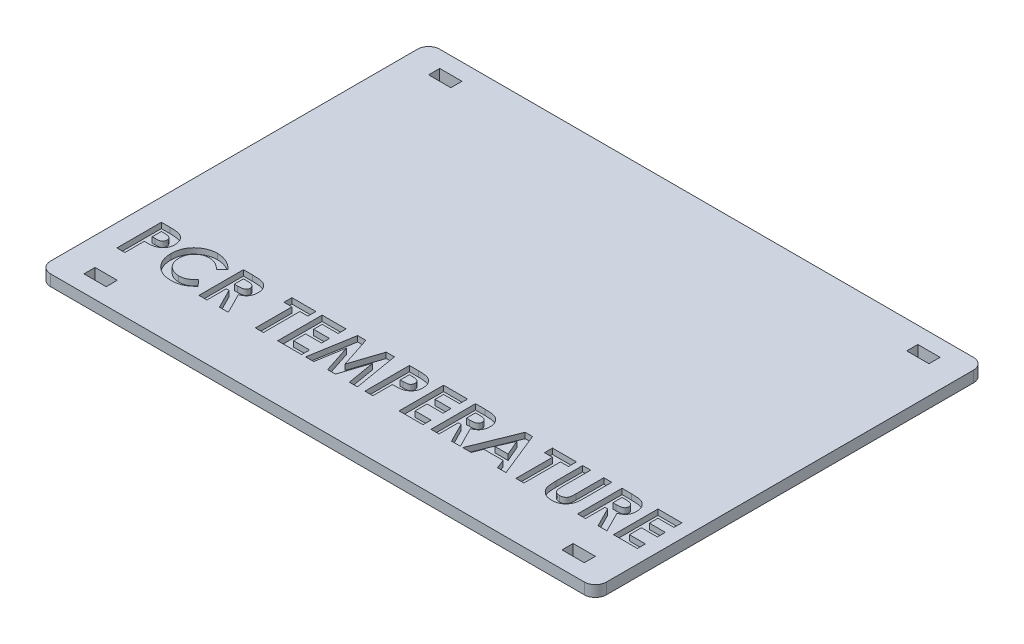
SolidWorks part; units mm, degrees
ref_plane "Front Plane" through (0, 0, 0) normal (0, 0, 1) x (1, 0, 0)
ref_plane "Top Plane" through (0, 0, 0) normal (0, 1, 0) x (1, 0, 0)
ref_plane "Right Plane" through (0, 0, 0) normal (1, 0, 0) x (0, 0, -1)
sketch "Sketch1" plane through (0, 0, 0) normal (0, 1, 0) x (1, 0, 0)
  line L1 (-48, 35) -> (48, 35)
  line L2 (-50, 33) -> (-50, -33)
  line L3 (-48, -35) -> (48, -35)
  line L4 (50, 33) -> (50, -33)
  line L5 (-50, 35) -> (50, -35) construction
  line L6 (-50, -35) -> (50, 35) construction
  arc A0 (-50, -33) -> (-48, -35) centre (-48, -33) ccw
  arc A1 (48, -35) -> (50, -33) centre (48, -33) ccw
  arc A2 (48, 35) -> (50, 33) centre (48, 33) cw
  arc A3 (-48, 35) -> (-50, 33) centre (-48, 33) ccw
  point P0 (0, 0)
  dimension "D3" = 2
  dimension "D1" = 100
  dimension "D2" = 70
extrude "Boss-Extrude1" add sketch "Sketch1" along normal blind 2
sketch "Sketch4" plane through (0, 0, 0) normal (0, -1, 0) x (-1, 0, 0)
  line L1 (46, 33) -> (-46, 33)
  line L2 (48, 31) -> (48, -31)
  line L3 (46, -33) -> (-46, -33)
  line L4 (-48, 31) -> (-48, -31)
  line L5 (48, 33) -> (-48, -33) construction
  line L6 (48, -33) -> (-48, 33) construction
  line L7 (46, -31) -> (-46, -31)
  line L8 (46, -31) -> (46, 31)
  line L9 (46, 31) -> (-46, 31)
  line L10 (-46, -31) -> (-46, 31)
  line L11 (46, -31) -> (-46, 31) construction
  line L12 (46, 31) -> (-46, -31) construction
  arc A0 (46, 33) -> (48, 31) centre (46, 31) cw
  arc A1 (-46, 33) -> (-48, 31) centre (-46, 31) ccw
  arc A2 (-46, -33) -> (-48, -31) centre (-46, -31) cw
  arc A3 (48, -31) -> (46, -33) centre (46, -31) cw
  point P0 (0, 0)
  point P18 (0, 0)
  dimension "D3" = 2
  dimension "D1" = 66
  dimension "D2" = 96
  dimension "D4" = 2
  dimension "D5" = 2
extrude "Boss-Extrude2" add sketch "Sketch4" along normal blind 2 contours L10 L7 L8 L9 | A3 L2 A0 L1 A1 L4 A2 L3
sketch "Sketch5" plane through (0, 2, 0) normal (0, 1, 0) x (1, 0, 0)
  line L0 (0, 0) -> (0, 35) construction
  line L1 (-41, 30) -> (-45, 30)
  line L2 (-41, 30) -> (-41, 32)
  line L3 (-41, 32) -> (-45, 32)
  line L4 (-45, 30) -> (-45, 32)
  line L5 (48, 35) -> (-48, 35) construction
  line L6 (-50, 33) -> (-50, -33) construction
  line L7 (41, 32) -> (45, 32)
  line L8 (45, 30) -> (45, 32)
  line L9 (41, 30) -> (45, 30)
  line L10 (41, 30) -> (41, 32)
  line L11 (0, 0) -> (50, 0) construction
  line L12 (50, -33) -> (50, 33) construction
  line L13 (41, -30) -> (41, -32)
  line L14 (41, -30) -> (45, -30)
  line L15 (45, -30) -> (45, -32)
  line L16 (41, -32) -> (45, -32)
  line L17 (-41, -32) -> (-45, -32)
  line L18 (-45, -30) -> (-45, -32)
  line L19 (-41, -30) -> (-45, -30)
  line L20 (-41, -30) -> (-41, -32)
  dimension "D1" = 4
  dimension "D2" = 2
  dimension "D3" = 5
  dimension "D4" = 3
extrude "Cut-Extrude1" cut sketch "Sketch5" against normal through all
sketch "Sketch6" plane through (0, 2, 0) normal (0, 1, 0) x (1, 0, 0)
  text T0 "<b>PCR TEMPERATURE</b>" font "Century Gothic" height 8
  point P1 (-33.8471, -30.8388)
  point P2 (-41.7643, -27.5956)
  point P3 (-45.866, -27.4049)
  point P4 (0, 0)
  point P5 (0, 0)
extrude "Cut-Extrude2" cut sketch "Sketch6" against normal blind 1
